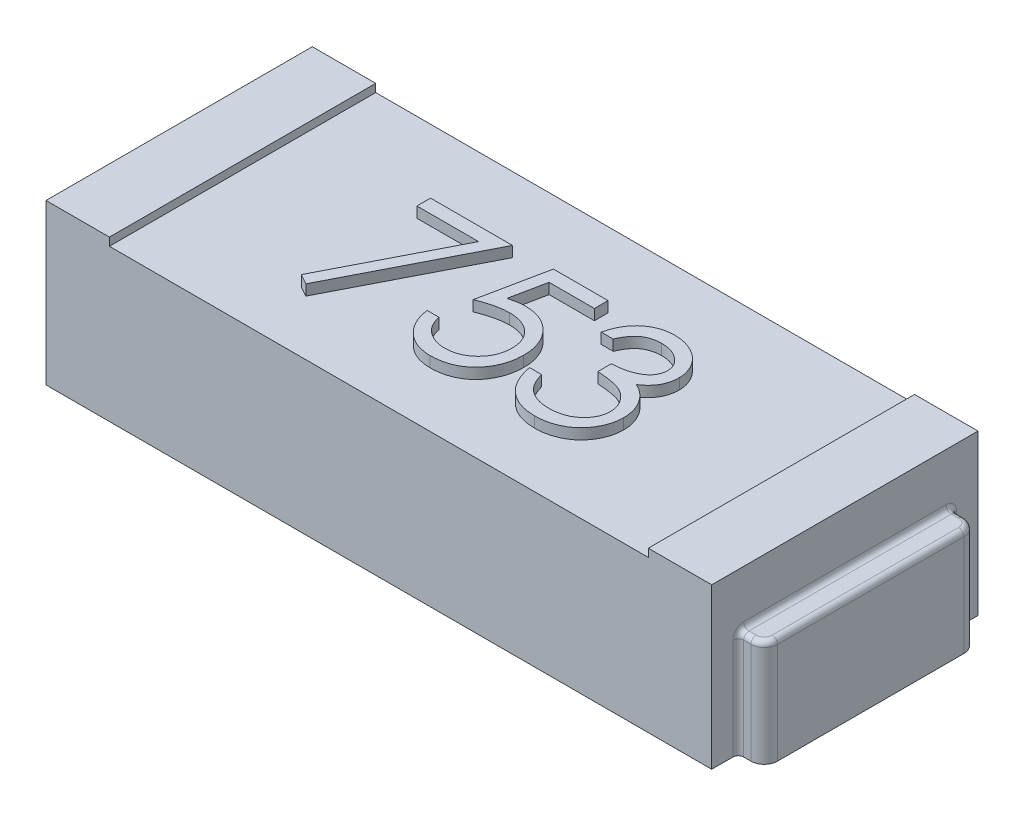
SolidWorks part; units mm, degrees
ref_plane "Plan de face" through (0, 0, 0) normal (0, 0, 1) x (1, 0, 0)
ref_plane "Plan de dessus" through (0, 0, 0) normal (0, 1, 0) x (1, 0, 0)
ref_plane "Plan de droite" through (0, 0, 0) normal (1, 0, 0) x (0, 0, -1)
sketch "Esquisse1" plane through (0, 0, 0) normal (0, 1, 0) x (1, 0, 0)
  line L1 (1.25, -0.5) -> (-1.25, -0.5)
  line L2 (1.25, -0.5) -> (1.25, 0.5)
  line L3 (1.25, 0.5) -> (-1.25, 0.5)
  line L4 (-1.25, -0.5) -> (-1.25, 0.5)
  line L5 (1.25, -0.5) -> (-1.25, 0.5) construction
  line L6 (1.25, 0.5) -> (-1.25, -0.5) construction
  point P0 (0, 0)
  dimension "D1" = 2.5
  dimension "D2" = 1
extrude "Boss.-Extru.1" add sketch "Esquisse1" along normal blind 0.6
sketch "Esquisse2" plane through (0, 0.6, 0) normal (0, 1, 0) x (1, 0, 0)
  line L0 (1.25, 0.5) -> (-1.25, 0.5) construction
  line L1 (1.0118, -0.5) -> (-1.0118, -0.5)
  line L2 (1.0118, -0.5) -> (1.0118, 0.5)
  line L3 (1.0118, 0.5) -> (-1.0118, 0.5)
  line L4 (-1.0118, -0.5) -> (-1.0118, 0.5)
  line L5 (1.0118, -0.5) -> (-1.0118, 0.5) construction
  line L6 (1.0118, 0.5) -> (-1.0118, -0.5) construction
  point P0 (0, 0)
extrude "Enlèv. mat.-Extru.1" cut sketch "Esquisse2" against normal blind 0.03
sketch "Esquisse3" plane through (0, 0, 0) normal (0, 1, 0) x (1, 0, 0)
  line L0 (1.25, -0.5) -> (1.25, 0.5) construction
  line L1 (1.25, 0.4) -> (1.2971, 0.4)
  line L2 (1.25, 0.4) -> (1.25, -0.4)
  line L3 (1.25, -0.4) -> (1.2971, -0.4)
  line L4 (1.3471, 0.35) -> (1.3471, -0.35)
  line L5 (1.25, 0.5) -> (1.0118, 0.5) construction
  line L6 (1.0118, -0.5) -> (1.25, -0.5) construction
  arc A0 (1.2971, -0.4) -> (1.3471, -0.35) centre (1.2971, -0.35) ccw
  arc A1 (1.2971, 0.4) -> (1.3471, 0.35) centre (1.2971, 0.35) cw
  dimension "D1" = 0.05
  dimension "D2" = 0.1
  dimension "D3" = 0.1
extrude "Boss.-Extru.2" add sketch "Esquisse3" along normal blind 0.4
fillet "Congé1" radius 0.02 8 edges at (1.25, 0.2, -0.4) (1.25, 0.2, 0.4) (1.2736, 0.4, -0.4) (1.3325, 0.4, -0.3854) (1.3471, 0.4, 0) (1.3325, 0.4, 0.3854) (1.2736, 0.4, 0.4) (1.25, 0.4, 0)
mirror "Symétrie2" about plane through (0, 0, 0) normal (1, 0, 0) of "Congé1", "Boss.-Extru.2"
sketch "Esquisse4" plane through (0, 0.57, 0) normal (0, 1, 0) x (1, 0, 0)
  line L0 (0.7576, -0.2803) -> (-0.7576, -0.2803) construction
  text T0 "753" font "Century Gothic" height 0.5
  point P3 (0, -0.2803)
extrude "Boss.-Extru.3" add sketch "Esquisse4" along normal blind 0.04
